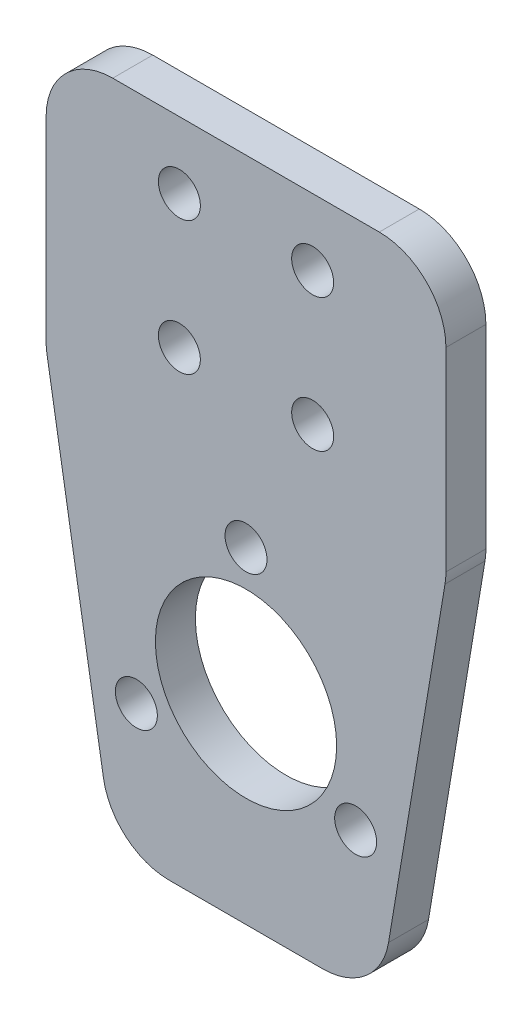
SolidWorks part; units mm, degrees
ref_plane "前视基准面" through (0, 0, 0) normal (0, 0, 1) x (1, 0, 0)
ref_plane "上视基准面" through (0, 0, 0) normal (0, 1, 0) x (1, 0, 0)
ref_plane "右视基准面" through (0, 0, 0) normal (1, 0, 0) x (0, 0, -1)
other "Configuration Table"
sketch "草图1" plane through (0, 0, 0) normal (0, 0, 1) x (1, 0, 0)
  line L0 (0, 0) -> (0, -20)
  line L4 (30, -20) -> (30, 0)
  line L5 (30, 0) -> (0, 0)
  line L6 (15, 0) -> (15, -50) construction
  line L7 (30, -20) -> (25, -50)
  line L8 (0, -20) -> (5, -50)
  line L9 (25, -50) -> (5, -50)
  dimension "D1" = 20
  dimension "D2" = 30
  dimension "D3" = 20
  dimension "D4" = 50
extrude "凸台-拉伸1" add sketch "草图1" along normal blind 3
sketch "草图2" plane through (0, 0, 3) normal (0, 0, 1) x (1, 0, 0)
  line L0 (0, -10) -> (30, -10) construction
  line L1 (0, 0) -> (0, -20) construction
  line L2 (30, -20) -> (30, 0) construction
  line L3 (15, 0) -> (15, -50) construction
  line L4 (30, 0) -> (0, 0) construction
  line L6 (5, -50) -> (25, -50) construction
  circle A1 centre (10, -5) radius 1.575
  circle A2 centre (10, -15) radius 1.575
  circle A5 centre (20, -15) radius 1.575
  circle A6 centre (20, -5) radius 1.575
  circle A8 centre (15, -35) radius 6.8
  circle A9 centre (15, -25.5) radius 1.575
  circle A10 centre (23.2272, -39.75) radius 1.575
  circle A11 centre (6.7728, -39.75) radius 1.575
  point P40 (15, -35)
  dimension "D1" = 5
  dimension "D5" = 13.6
  dimension "D8" = 3.15
  dimension "D3" = 3.15
  dimension "D2" = 5
  dimension "D6" = 15
  dimension "D7" = 9.5
  dimension "D9" = 3
extrude "切除-拉伸2" cut sketch "草图2" against normal through all
fillet "圆角1" radius 5 6 edges at (25, -50, 1.5) (5, -50, 1.5) (0, -20, 1.5) (30, -20, 1.5) (30, 0, 1.5) (0, 0, 1.5)
